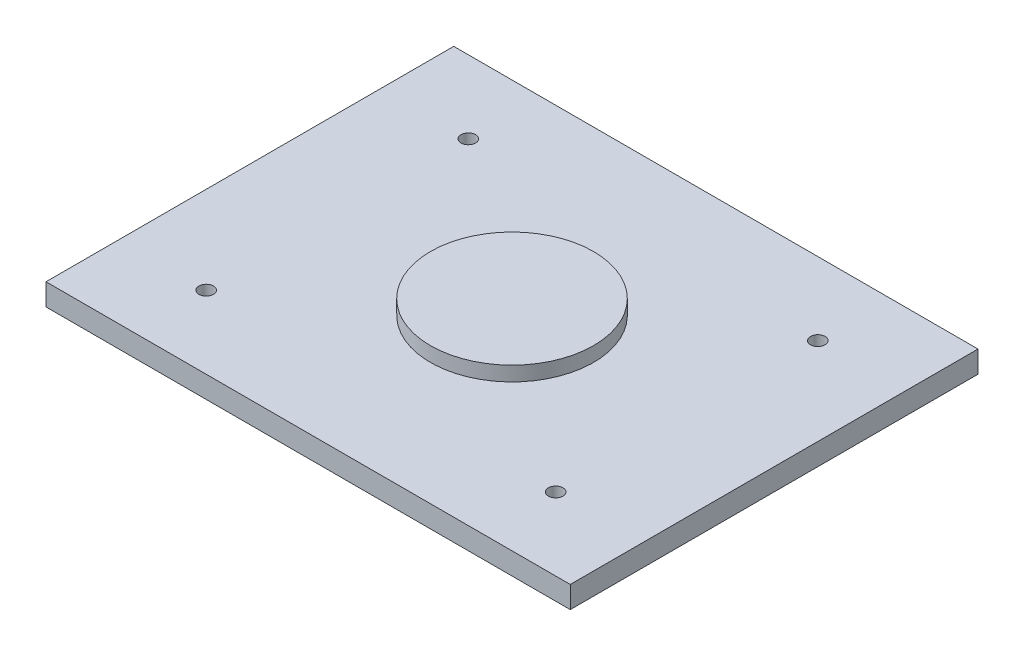
SolidWorks part; units mm, degrees
material "6061-T6 (SS)"
ref_plane "Front Plane" through (0, 0, 0) normal (0, 0, 1) x (1, 0, 0)
ref_plane "Top Plane" through (0, 0, 0) normal (0, 1, 0) x (1, 0, 0)
ref_plane "Right Plane" through (0, 0, 0) normal (1, 0, 0) x (0, 0, -1)
sketch "Sketch1" plane through (0, 0, 0) normal (0, 1, 0) x (1, 0, 0)
  line L1 (-114.3, -88.9) -> (114.3, -88.9)
  line L2 (-114.3, -88.9) -> (-114.3, 88.9)
  line L3 (-114.3, 88.9) -> (114.3, 88.9)
  line L4 (114.3, -88.9) -> (114.3, 88.9)
  line L5 (-114.3, -88.9) -> (114.3, 88.9) construction
  line L6 (-114.3, 88.9) -> (114.3, -88.9) construction
  point P0 (0, 0)
  dimension "D1" = 228.6
  dimension "D2" = 177.8
extrude "Boss-Extrude1" add sketch "Sketch1" along normal blind 9.525
hole_wizard "1/4-20 Tapped Hole1" positions "Sketch3" profile "Sketch4" tap size "1/4-20" standard "Ansi Inch" end condition through all
sketch "Sketch3" plane through (0, 9.525, 0) normal (0, 1, 0) x (-1, 0, 0)
  line L0 (-76.2, 57.15) -> (76.2, -57.15) construction
  line L3 (-76.2, -57.15) -> (76.2, 57.15) construction
  line L6 (-76.2, 57.15) -> (0, 0) construction
  line L7 (0, 0) -> (76.2, -57.15) construction
  point P0 (76.2, -57.15)
  point P1 (76.2, 57.15)
  point P3 (-76.2, 57.15)
  point P5 (-76.2, -57.15)
  dimension "D1" = 114.3
  dimension "D2" = 152.4
sketch "Sketch4" plane through (-76.2, 9.525, -57.15) normal (1, 0, 0) x (0, 0, 1)
  line L0 (0, 0) -> (0, 9.525)
  line L1 (0, 9.525) -> (3.175, 9.525)
  line L2 (3.175, 9.525) -> (3.175, 0)
  line L5 (3.175, 0) -> (0, 0)
  line L11 (0, -6.35) -> (0, 107.95) construction
  dimension "Thread Major Dia." = 6.35
  dimension "Thru Tap Drill Depth" = 9.525
sketch "Sketch5" plane through (0, 9.525, 0) normal (0, 1, 0) x (1, 0, 0)
  circle A0 centre (0, 0) radius 35.56
  dimension "D1" = 71.12
extrude "Boss-Extrude2" add sketch "Sketch5" along normal blind 6.35
